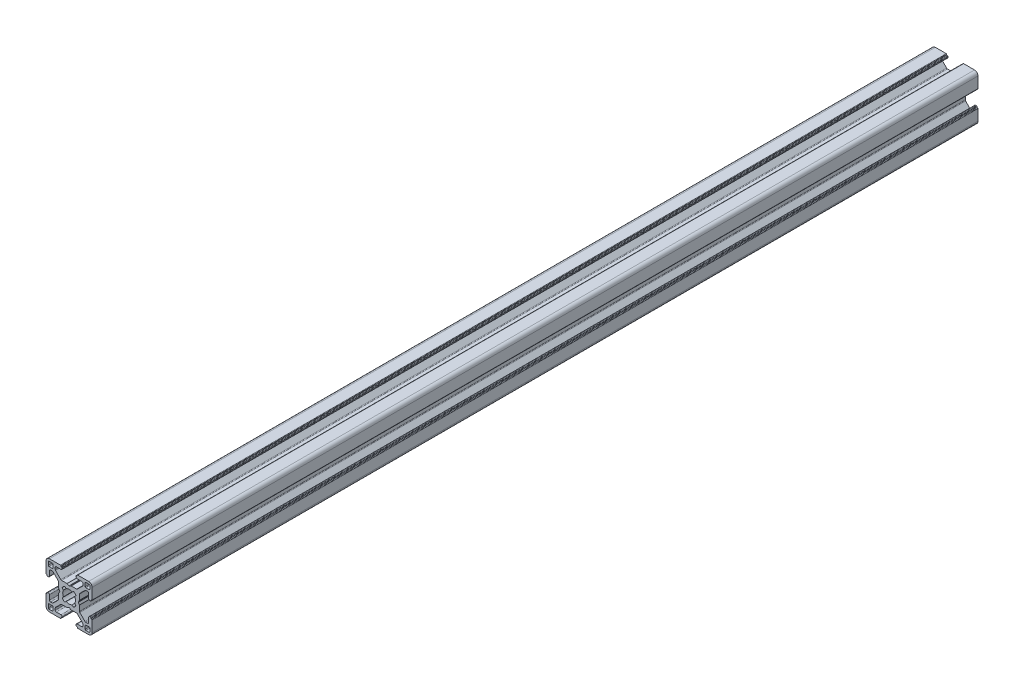
SolidWorks part; units mm, degrees
material "6063-O, Barra estrusa (SS)"
ref_plane "Piano frontale" through (0, 0, 0) normal (0, 0, 1) x (1, 0, 0)
ref_plane "Piano superiore" through (0, 0, 0) normal (0, 1, 0) x (1, 0, 0)
ref_plane "Piano destro" through (0, 0, 0) normal (1, 0, 0) x (0, 0, -1)
ref_plane "Piano1" through (0, 0, 100) normal (0, 0, 1) x (1, 0, 0)
sketch "Schizzo1" plane through (0, 0, 100) normal (0, 0, 1) x (1, 0, 0)
  line L0 (-1.9139, 2.9896) -> (-1.2582, 2.4453)
  line L1 (1.2582, 2.4453) -> (1.9139, 2.9896)
  line L2 (2.9922, 1.9099) -> (2.4453, 1.2582)
  line L3 (2.4453, -1.2582) -> (2.9922, -1.9099)
  line L4 (1.9139, -2.9896) -> (1.2582, -2.4453)
  line L5 (-1.2582, -2.4453) -> (-1.9139, -2.9896)
  line L6 (-2.9922, -1.9099) -> (-2.4453, -1.2582)
  line L7 (-2.4453, 1.2582) -> (-2.9922, 1.9099)
  line L8 (-9.3, 3) -> (-9, 3)
  line L9 (-8.5, 3.5) -> (-8.5, 5.5)
  line L10 (-8, 6) -> (-7.2678, 6)
  line L11 (-6.9142, 5.8536) -> (-4.6464, 3.5858)
  line L12 (-4.5, 3.2322) -> (-4.5, 0.9536)
  line L13 (-4.4732, 0.8536) -> (-4.0381, 0.1)
  line L14 (-4.0381, -0.1) -> (-4.4732, -0.8536)
  line L15 (-4.5, -0.9536) -> (-4.5, -3.2322)
  line L16 (-4.6464, -3.5858) -> (-6.9142, -5.8536)
  line L17 (-7.2678, -6) -> (-8, -6)
  line L18 (-8.5, -5.5) -> (-8.5, -3.5)
  line L19 (-9, -3) -> (-9.3, -3)
  line L20 (-9.5, -3.2) -> (-9.5, -3.35)
  line L21 (-9.7, -3.55) -> (-9.8, -3.55)
  line L22 (-10, -3.75) -> (-10, -8.5)
  line L23 (-8.5, -10) -> (-3.75, -10)
  line L24 (-3.55, -9.8) -> (-3.55, -9.7)
  line L25 (-3.35, -9.5) -> (-3.2, -9.5)
  line L26 (-3, -9.3) -> (-3, -9)
  line L27 (-3.5, -8.5) -> (-5.5, -8.5)
  line L28 (-6, -8) -> (-6, -7.2678)
  line L29 (-5.8536, -6.9142) -> (-3.5858, -4.6464)
  line L30 (-3.2322, -4.5) -> (-0.9536, -4.5)
  line L31 (-0.8536, -4.4732) -> (-0.1, -4.0381)
  line L32 (0.1, -4.0381) -> (0.8536, -4.4732)
  line L33 (0.9536, -4.5) -> (3.2322, -4.5)
  line L34 (3.5858, -4.6464) -> (5.8536, -6.9142)
  line L35 (6, -7.2678) -> (6, -8)
  line L36 (5.5, -8.5) -> (3.5, -8.5)
  line L37 (3, -9) -> (3, -9.3)
  line L38 (3.2, -9.5) -> (3.35, -9.5)
  line L39 (3.55, -9.7) -> (3.55, -9.8)
  line L40 (3.75, -10) -> (8.5, -10)
  line L41 (10, -8.5) -> (10, -3.75)
  line L42 (9.8, -3.55) -> (9.7, -3.55)
  line L43 (9.5, -3.35) -> (9.5, -3.2)
  line L44 (9.3, -3) -> (9, -3)
  line L45 (8.5, -3.5) -> (8.5, -5.5)
  line L46 (8, -6) -> (7.2678, -6)
  line L47 (6.9142, -5.8536) -> (4.6464, -3.5858)
  line L48 (4.5, -3.2322) -> (4.5, -0.9536)
  line L49 (4.4732, -0.8536) -> (4.0381, -0.1)
  line L50 (4.0381, 0.1) -> (4.4732, 0.8536)
  line L51 (4.5, 0.9536) -> (4.5, 3.2322)
  line L52 (4.6464, 3.5858) -> (6.9142, 5.8536)
  line L53 (7.2678, 6) -> (8, 6)
  line L54 (8.5, 5.5) -> (8.5, 3.5)
  line L55 (9, 3) -> (9.3, 3)
  line L56 (9.5, 3.2) -> (9.5, 3.35)
  line L57 (9.7, 3.55) -> (9.8, 3.55)
  line L58 (10, 3.75) -> (10, 8.5)
  line L59 (8.5, 10) -> (3.75, 10)
  line L60 (3.55, 9.8) -> (3.55, 9.7)
  line L61 (3.35, 9.5) -> (3.2, 9.5)
  line L62 (3, 9.3) -> (3, 9)
  line L63 (3.5, 8.5) -> (5.5, 8.5)
  line L64 (6, 8) -> (6, 7.2678)
  line L65 (5.8536, 6.9142) -> (3.5858, 4.6464)
  line L66 (3.2322, 4.5) -> (0.9536, 4.5)
  line L67 (0.8536, 4.4732) -> (0.1, 4.0381)
  line L68 (-0.1, 4.0381) -> (-0.8536, 4.4732)
  line L69 (-0.9536, 4.5) -> (-3.2322, 4.5)
  line L70 (-3.5858, 4.6464) -> (-5.8536, 6.9142)
  line L71 (-6, 7.2678) -> (-6, 8)
  line L72 (-5.5, 8.5) -> (-3.5, 8.5)
  line L73 (-3, 9) -> (-3, 9.3)
  line L74 (-3.2, 9.5) -> (-3.35, 9.5)
  line L75 (-3.55, 9.7) -> (-3.55, 9.8)
  line L76 (-3.75, 10) -> (-8.5, 10)
  line L77 (-10, 8.5) -> (-10, 3.75)
  line L78 (-9.8, 3.55) -> (-9.7, 3.55)
  line L79 (-9.5, 3.35) -> (-9.5, 3.2)
  line L80 (8.7, 7) -> (7.3, 7)
  line L81 (-7.3, 7) -> (-8.7, 7)
  line L82 (-7, 7.3) -> (-7, 8.7)
  line L83 (-7.3, 9) -> (-8.7, 9)
  line L84 (-9, 7.3) -> (-9, 8.7)
  line L85 (9, 7.3) -> (9, 8.7)
  line L86 (8.7, 9) -> (7.3, 9)
  line L87 (7, 7.3) -> (7, 8.7)
  line L88 (8.7, -9) -> (7.3, -9)
  line L89 (9, -8.7) -> (9, -7.3)
  line L90 (8.7, -7) -> (7.3, -7)
  line L91 (7, -8.7) -> (7, -7.3)
  line L92 (-7.3, -9) -> (-8.7, -9)
  line L93 (-7, -8.7) -> (-7, -7.3)
  line L94 (-7.3, -7) -> (-8.7, -7)
  line L95 (-9, -8.7) -> (-9, -7.3)
  arc A0 (-1.2582, 2.4453) -> (1.2582, 2.4453) centre (0, 0) cw
  arc A1 (1.9139, 2.9896) -> (2.9922, 1.9099) centre (0, 0) cw
  arc A2 (2.4453, 1.2582) -> (2.4453, -1.2582) centre (0, 0) cw
  arc A3 (2.9922, -1.9099) -> (1.9139, -2.9896) centre (0, 0) cw
  arc A4 (1.2582, -2.4453) -> (-1.2582, -2.4453) centre (0, 0) cw
  arc A5 (-1.9139, -2.9896) -> (-2.9922, -1.9099) centre (0, 0) cw
  arc A6 (-2.4453, -1.2582) -> (-2.4453, 1.2582) centre (0, 0) cw
  arc A7 (-2.9922, 1.9099) -> (-1.9139, 2.9896) centre (0, 0) cw
  arc A8 (-9.5, 3.2) -> (-9.3, 3) centre (-9.3, 3.2) ccw
  arc A9 (-9, 3) -> (-8.5, 3.5) centre (-9, 3.5) ccw
  arc A10 (-8.5, 5.5) -> (-8, 6) centre (-8, 5.5) cw
  arc A11 (-7.2678, 6) -> (-6.9142, 5.8536) centre (-7.2678, 5.5) cw
  arc A12 (-4.6464, 3.5858) -> (-4.5, 3.2322) centre (-5, 3.2322) cw
  arc A13 (-4.5, 0.9536) -> (-4.4732, 0.8536) centre (-4.3, 0.9536) ccw
  arc A14 (-4.0381, 0.1) -> (-4.0381, -0.1) centre (-4.2113, 0) cw
  arc A15 (-4.4732, -0.8536) -> (-4.5, -0.9536) centre (-4.3, -0.9536) ccw
  arc A16 (-4.5, -3.2322) -> (-4.6464, -3.5858) centre (-5, -3.2322) cw
  arc A17 (-6.9142, -5.8536) -> (-7.2678, -6) centre (-7.2678, -5.5) cw
  arc A18 (-8, -6) -> (-8.5, -5.5) centre (-8, -5.5) cw
  arc A19 (-8.5, -3.5) -> (-9, -3) centre (-9, -3.5) ccw
  arc A20 (-9.3, -3) -> (-9.5, -3.2) centre (-9.3, -3.2) ccw
  arc A21 (-9.5, -3.35) -> (-9.7, -3.55) centre (-9.7, -3.35) cw
  arc A22 (-9.8, -3.55) -> (-10, -3.75) centre (-9.8, -3.75) ccw
  arc A23 (-10, -8.5) -> (-8.5, -10) centre (-8.5, -8.5) ccw
  arc A24 (-3.75, -10) -> (-3.55, -9.8) centre (-3.75, -9.8) ccw
  arc A25 (-3.55, -9.7) -> (-3.35, -9.5) centre (-3.35, -9.7) cw
  arc A26 (-3.2, -9.5) -> (-3, -9.3) centre (-3.2, -9.3) ccw
  arc A27 (-3, -9) -> (-3.5, -8.5) centre (-3.5, -9) ccw
  arc A28 (-5.5, -8.5) -> (-6, -8) centre (-5.5, -8) cw
  arc A29 (-6, -7.2678) -> (-5.8536, -6.9142) centre (-5.5, -7.2678) cw
  arc A30 (-3.5858, -4.6464) -> (-3.2322, -4.5) centre (-3.2322, -5) cw
  arc A31 (-0.9536, -4.5) -> (-0.8536, -4.4732) centre (-0.9536, -4.3) ccw
  arc A32 (-0.1, -4.0381) -> (0.1, -4.0381) centre (0, -4.2113) cw
  arc A33 (0.8536, -4.4732) -> (0.9536, -4.5) centre (0.9536, -4.3) ccw
  arc A34 (3.2322, -4.5) -> (3.5858, -4.6464) centre (3.2322, -5) cw
  arc A35 (5.8536, -6.9142) -> (6, -7.2678) centre (5.5, -7.2678) cw
  arc A36 (6, -8) -> (5.5, -8.5) centre (5.5, -8) cw
  arc A37 (3.5, -8.5) -> (3, -9) centre (3.5, -9) ccw
  arc A38 (3, -9.3) -> (3.2, -9.5) centre (3.2, -9.3) ccw
  arc A39 (3.35, -9.5) -> (3.55, -9.7) centre (3.35, -9.7) cw
  arc A40 (3.55, -9.8) -> (3.75, -10) centre (3.75, -9.8) ccw
  arc A41 (8.5, -10) -> (10, -8.5) centre (8.5, -8.5) ccw
  arc A42 (10, -3.75) -> (9.8, -3.55) centre (9.8, -3.75) ccw
  arc A43 (9.7, -3.55) -> (9.5, -3.35) centre (9.7, -3.35) cw
  arc A44 (9.5, -3.2) -> (9.3, -3) centre (9.3, -3.2) ccw
  arc A45 (9, -3) -> (8.5, -3.5) centre (9, -3.5) ccw
  arc A46 (8.5, -5.5) -> (8, -6) centre (8, -5.5) cw
  arc A47 (7.2678, -6) -> (6.9142, -5.8536) centre (7.2678, -5.5) cw
  arc A48 (4.6464, -3.5858) -> (4.5, -3.2322) centre (5, -3.2322) cw
  arc A49 (4.5, -0.9536) -> (4.4732, -0.8536) centre (4.3, -0.9536) ccw
  arc A50 (4.0381, -0.1) -> (4.0381, 0.1) centre (4.2113, 0) cw
  arc A51 (4.4732, 0.8536) -> (4.5, 0.9536) centre (4.3, 0.9536) ccw
  arc A52 (4.5, 3.2322) -> (4.6464, 3.5858) centre (5, 3.2322) cw
  arc A53 (6.9142, 5.8536) -> (7.2678, 6) centre (7.2678, 5.5) cw
  arc A54 (8, 6) -> (8.5, 5.5) centre (8, 5.5) cw
  arc A55 (8.5, 3.5) -> (9, 3) centre (9, 3.5) ccw
  arc A56 (9.3, 3) -> (9.5, 3.2) centre (9.3, 3.2) ccw
  arc A57 (9.5, 3.35) -> (9.7, 3.55) centre (9.7, 3.35) cw
  arc A58 (9.8, 3.55) -> (10, 3.75) centre (9.8, 3.75) ccw
  arc A59 (10, 8.5) -> (8.5, 10) centre (8.5, 8.5) ccw
  arc A60 (3.75, 10) -> (3.55, 9.8) centre (3.75, 9.8) ccw
  arc A61 (3.55, 9.7) -> (3.35, 9.5) centre (3.35, 9.7) cw
  arc A62 (3.2, 9.5) -> (3, 9.3) centre (3.2, 9.3) ccw
  arc A63 (3, 9) -> (3.5, 8.5) centre (3.5, 9) ccw
  arc A64 (5.5, 8.5) -> (6, 8) centre (5.5, 8) cw
  arc A65 (6, 7.2678) -> (5.8536, 6.9142) centre (5.5, 7.2678) cw
  arc A66 (3.5858, 4.6464) -> (3.2322, 4.5) centre (3.2322, 5) cw
  arc A67 (0.9536, 4.5) -> (0.8536, 4.4732) centre (0.9536, 4.3) ccw
  arc A68 (0.1, 4.0381) -> (-0.1, 4.0381) centre (0, 4.2113) cw
  arc A69 (-0.8536, 4.4732) -> (-0.9536, 4.5) centre (-0.9536, 4.3) ccw
  arc A70 (-3.2322, 4.5) -> (-3.5858, 4.6464) centre (-3.2322, 5) cw
  arc A71 (-5.8536, 6.9142) -> (-6, 7.2678) centre (-5.5, 7.2678) cw
  arc A72 (-6, 8) -> (-5.5, 8.5) centre (-5.5, 8) cw
  arc A73 (-3.5, 8.5) -> (-3, 9) centre (-3.5, 9) ccw
  arc A74 (-3, 9.3) -> (-3.2, 9.5) centre (-3.2, 9.3) ccw
  arc A75 (-3.35, 9.5) -> (-3.55, 9.7) centre (-3.35, 9.7) cw
  arc A76 (-3.55, 9.8) -> (-3.75, 10) centre (-3.75, 9.8) ccw
  arc A77 (-8.5, 10) -> (-10, 8.5) centre (-8.5, 8.5) ccw
  arc A78 (-10, 3.75) -> (-9.8, 3.55) centre (-9.8, 3.75) ccw
  arc A79 (-9.7, 3.55) -> (-9.5, 3.35) centre (-9.7, 3.35) cw
  arc A80 (-8.7, 7) -> (-9, 7.3) centre (-8.7, 7.3) cw
  arc A81 (-7, 8.7) -> (-7.3, 9) centre (-7.3, 8.7) ccw
  arc A82 (-7.3, 7) -> (-7, 7.3) centre (-7.3, 7.3) ccw
  arc A83 (-8.7, 9) -> (-9, 8.7) centre (-8.7, 8.7) ccw
  arc A84 (7.3, 7) -> (7, 7.3) centre (7.3, 7.3) cw
  arc A85 (9, 8.7) -> (8.7, 9) centre (8.7, 8.7) ccw
  arc A86 (8.7, 7) -> (9, 7.3) centre (8.7, 7.3) ccw
  arc A87 (7.3, 9) -> (7, 8.7) centre (7.3, 8.7) ccw
  arc A88 (7.3, -9) -> (7, -8.7) centre (7.3, -8.7) cw
  arc A89 (9, -7.3) -> (8.7, -7) centre (8.7, -7.3) ccw
  arc A90 (8.7, -9) -> (9, -8.7) centre (8.7, -8.7) ccw
  arc A91 (7.3, -7) -> (7, -7.3) centre (7.3, -7.3) ccw
  arc A92 (-8.7, -9) -> (-9, -8.7) centre (-8.7, -8.7) cw
  arc A93 (-7, -7.3) -> (-7.3, -7) centre (-7.3, -7.3) ccw
  arc A94 (-7.3, -9) -> (-7, -8.7) centre (-7.3, -8.7) ccw
  arc A95 (-8.7, -7) -> (-9, -7.3) centre (-8.7, -7.3) ccw
  dimension "D1" = 0.3
  dimension "D2" = 1
  dimension "D3" = 1
  dimension "D4" = 1
  dimension "D7" = 1
  dimension "D8" = 1
  dimension "D9" = 1
  dimension "D10" = 1
  dimension "D5" = 2
  dimension "D6" = 2
extrude "Estrusione-Estrusione1" add sketch "Schizzo1" against normal blind 384
